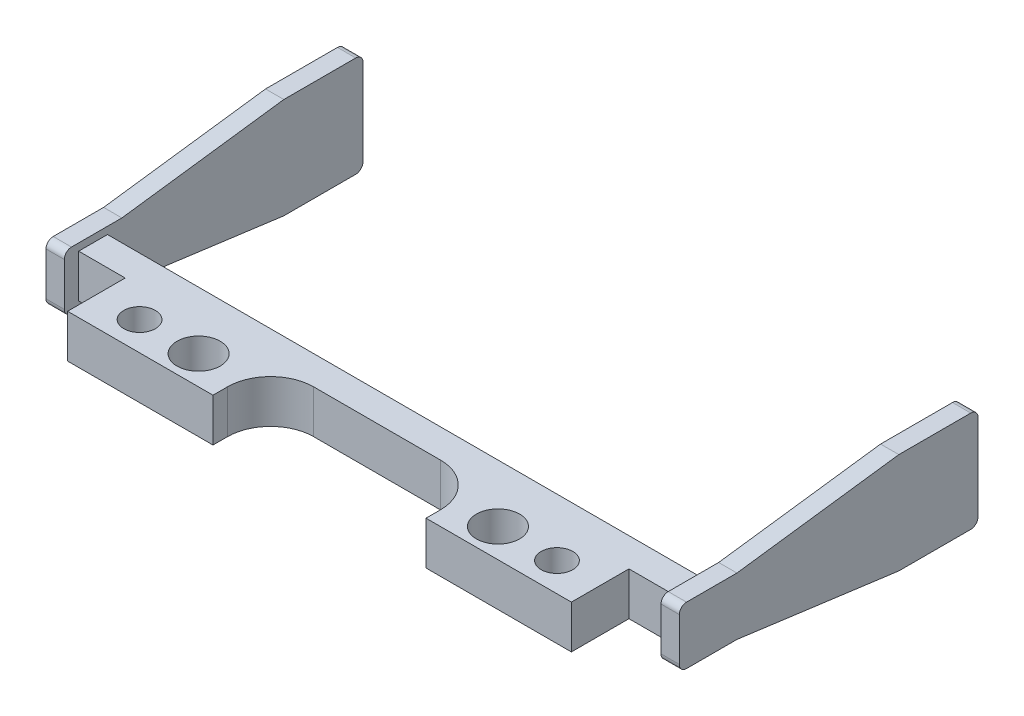
SolidWorks part; units mm, degrees
ref_plane "Front Plane" through (0, 0, 0) normal (0, 0, 1) x (1, 0, 0)
ref_plane "Top Plane" through (0, 0, 0) normal (0, 1, 0) x (1, 0, 0)
ref_plane "Right Plane" through (0, 0, 0) normal (1, 0, 0) x (0, 0, -1)
sketch "Sketch1" plane through (0, 0, 0) normal (0, 1, 0) x (1, 0, 0)
  line L0 (-220, -10) -> (-217.7309, -10) construction
  line L1 (-220, 10) -> (220, 10)
  line L2 (-220, 10) -> (-220, -10)
  line L3 (-220, -10) -> (220, -10)
  line L4 (220, 10) -> (220, -10)
  line L5 (-220, 10) -> (220, -10) construction
  line L6 (-220, -10) -> (220, 10) construction
  line L7 (-175, -10) -> (-175, -50)
  line L8 (-217.7309, -10) -> (-182.7309, -10)
  line L9 (0, 10) -> (0, -72.7) construction
  line L10 (-175, -50) -> (-74, -50)
  line L11 (175, -10) -> (175, -50)
  line L12 (-175, -50) -> (-74, -50)
  line L13 (-215.4975, -10) -> (-204.6074, -10)
  line L14 (-74, -50) -> (-74, -10)
  line L15 (-175, -30) -> (-74, -30) construction
  line L16 (-175, -30) -> (-145, -30) construction
  line L17 (-74, -30) -> (-104, -30) construction
  line L18 (74, -50) -> (74, -10)
  line L19 (74, -50) -> (175, -50)
  circle A0 centre (-145, -30) radius 11
  circle A1 centre (-104, -30) radius 10
  circle A2 centre (145, -30) radius 11
  circle A3 centre (104, -30) radius 10
  point P0 (0, 0)
  dimension "D3" = 22
  dimension "D4" = 20
  dimension "D1" = 45
  dimension "D2" = 45
extrude "Boss-Extrude1" add sketch "Sketch1" along normal blind 30 contours L10 L14 L3 L7 A1 A0 | L4 L1 L2 L3 L8 | L18 L19 L11 L3 A2 A3
fillet "Fillet1" radius 30 1 edges at (-74, 15, 10)
fillet "Fillet2" radius 30 1 edges at (74, 15, 10)
sketch "Sketch2" plane through (220, 0, 0) normal (1, 0, 0) x (0, 0, -1)
  line L0 (10, 15) -> (-10, 15) construction
  line L1 (10, 30) -> (10, 0) construction
  line L2 (-10, 30) -> (-10, 0) construction
  line L3 (160, 15) -> (10, 15) construction
  line L4 (20.0092, 34.993) -> (-15.0162, 34.993)
  line L6 (20.0192, -4.998) -> (-15.0162, -4.998)
  line L7 (-20.0142, 29.995) -> (-20.0142, 0)
  line L8 (20.0092, 34.993) -> (-20.0142, -4.998) construction
  line L9 (20.0192, -4.998) -> (-20.0142, 34.993) construction
  line L13 (182.5, 50) -> (132.5, 50)
  line L16 (132.5, 50) -> (20.0092, 34.993)
  line L17 (132.5, -20) -> (20.0192, -4.998)
  line L18 (187.5, 45) -> (187.5, -15)
  line L19 (182.5, -20) -> (132.5, -20)
  line L21 (187.5, 50) -> (132.5, -20) construction
  line L22 (187.5, -20) -> (132.5, 50) construction
  arc A0 (187.5, -15) -> (182.5, -20) centre (182.5, -15) cw
  arc A1 (187.5, 45) -> (182.5, 50) centre (182.5, 45) ccw
  arc A6 (-20.0142, 0) -> (-15.0162, -4.998) centre (-15.0162, 0) ccw
  arc A7 (-20.0142, 29.995) -> (-15.0162, 34.993) centre (-15.0162, 29.995) cw
  point P6 (0, 15)
  point P7 (0, 15)
  point P12 (110, 15)
  dimension "D1" = 5
  dimension "D2" = 150
extrude "Boss-Extrude2" add sketch "Sketch2" against normal blind 12.7
pattern_linear "LPattern2" count 2 spacing 427.3 along (-1, 0, 0) of "Boss-Extrude2"
sketch "Sketch3" plane through (0, 30, 0) normal (0, 1, 0) x (1, 0, 0)
  circle A0 centre (-104, -30) radius 15
  circle A1 centre (104, -30) radius 15
  dimension "D1" = 30
  dimension "D2" = 30
extrude "Cut-Extrude1" cut sketch "Sketch3" against normal up to next
